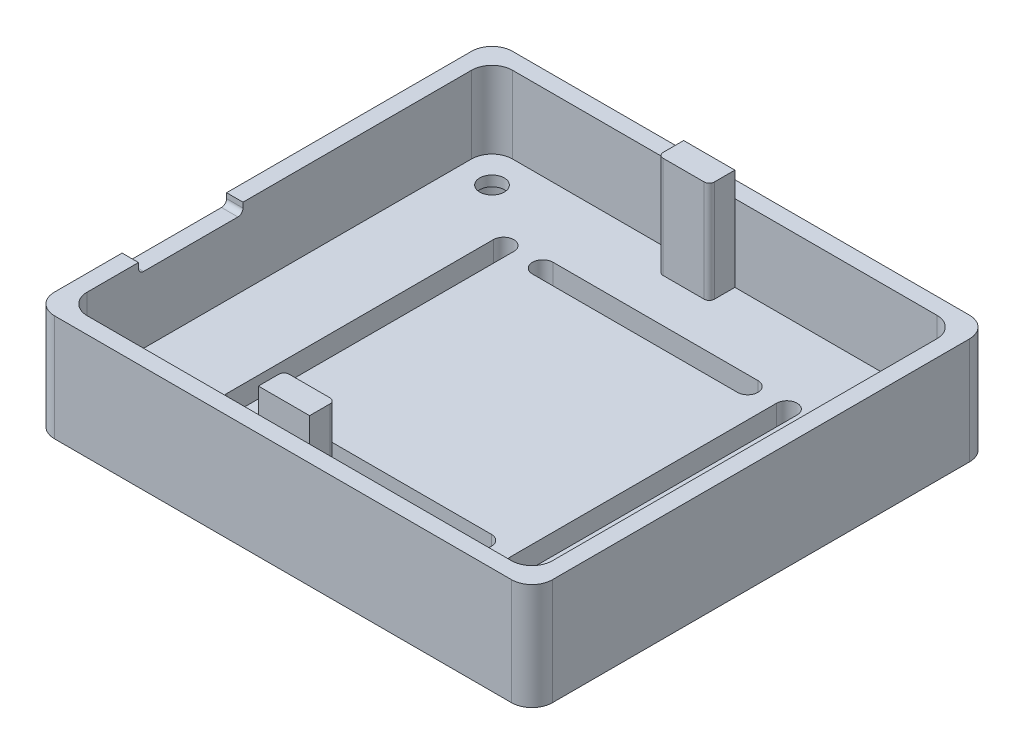
SolidWorks part; units mm, degrees
ref_plane "前视基准面" through (0, 0, 0) normal (0, 0, 1) x (1, 0, 0)
ref_plane "上视基准面" through (0, 0, 0) normal (0, 1, 0) x (1, 0, 0)
ref_plane "右视基准面" through (0, 0, 0) normal (1, 0, 0) x (0, 0, -1)
other "Configuration Table"
sketch "草图1" plane through (0, 0, 0) normal (0, 1, 0) x (1, 0, 0)
  line L1 (-22.3, -22.35) -> (22.3, -22.35)
  line L2 (-24.3, -20.35) -> (-24.3, 20.35)
  line L3 (-22.3, 22.35) -> (22.3, 22.35)
  line L4 (24.3, -20.35) -> (24.3, 20.35)
  line L5 (0, 22.35) -> (0, -22.35) construction
  line L6 (-24.3, 0) -> (24.3, 0) construction
  arc A0 (-22.3, -22.35) -> (-24.3, -20.35) centre (-22.3, -20.35) cw
  arc A1 (22.3, -22.35) -> (24.3, -20.35) centre (22.3, -20.35) ccw
  arc A2 (22.3, 22.35) -> (24.3, 20.35) centre (22.3, 20.35) cw
  arc A3 (-24.3, 20.35) -> (-22.3, 22.35) centre (-22.3, 20.35) cw
  point P0 (0, 0)
  point P6 (-24.3, -22.35)
  point P9 (24.3, -22.35)
  point P15 (-24.3, 22.35)
  dimension "D3" = 2
  dimension "D1" = 48.6
  dimension "D2" = 44.7
extrude "凸台-拉伸1" add sketch "草图1" along normal blind 10.4
sketch "草图2" plane through (0, 10.4, 0) normal (0, 1, 0) x (1, 0, 0)
  line L1 (-20.7, -20.75) -> (20.7, -20.75)
  line L2 (-22.7, -18.75) -> (-22.7, 18.75)
  line L3 (-20.7, 20.75) -> (20.7, 20.75)
  line L4 (22.7, -18.75) -> (22.7, 18.75)
  line L5 (0, 20.75) -> (0, -20.75) construction
  line L6 (-22.7, 0) -> (22.7, 0) construction
  arc A0 (20.7, -20.75) -> (22.7, -18.75) centre (20.7, -18.75) ccw
  arc A1 (-20.7, -20.75) -> (-22.7, -18.75) centre (-20.7, -18.75) cw
  arc A2 (20.7, 20.75) -> (22.7, 18.75) centre (20.7, 18.75) cw
  arc A3 (-22.7, 18.75) -> (-20.7, 20.75) centre (-20.7, 18.75) cw
  point P0 (0, 0)
  point P11 (22.7, 20.75)
  point P14 (-22.7, 20.75)
  dimension "D3" = 2
  dimension "D1" = 45.4
  dimension "D2" = 41.5
extrude "切除-拉伸1" cut sketch "草图2" against normal blind 7.5
sketch "草图3" plane through (0, 0, 0) normal (0, -1, 0) x (1, 0, 0)
  line L0 (-24.3, -20.35) -> (-24.3, 20.35) construction
  line L2 (22.3, -22.35) -> (-22.3, -22.35) construction
  line L3 (0, 0) -> (-33.4621, 0) construction
  line L4 (-1.5, 7.444) -> (-1.5, -25.453) construction
  line L5 (-22.7, -18.75) -> (-22.7, 18.75) construction
  circle A0 centre (-19.5, -17.55) radius 2.1
  circle A1 centre (-19.5, 17.55) radius 2.1
  circle A2 centre (16.5, 17.55) radius 2.1
  dimension "D1" = 4.8
  dimension "D2" = 4.8
  dimension "D3" = 21.2
extrude "切除-拉伸2" cut sketch "草图3" against normal blind 1.9
sketch "草图4" plane through (0, 0, 0) normal (0, -1, 0) x (1, 0, 0)
  line L0 (0, 0) -> (-34.7805, 0) construction
  line L1 (-1.5, 22.1974) -> (-1.5, -25.6414) construction
  line L2 (-22.7, -18.75) -> (-22.7, 18.75) construction
  circle A0 centre (-19.5, 17.55) radius 1.2
  circle A1 centre (-19.5, 17.55) radius 2.1 construction
  circle A2 centre (-19.5, -17.55) radius 1.2
  circle A3 centre (16.5, 17.55) radius 1.2
  dimension "D1" = 0
  dimension "D3" = 21.2
extrude "切除-拉伸3" cut sketch "草图4" against normal blind 3.2
sketch "草图5" plane through (0, 2.9, 0) normal (0, 1, 0) x (1, 0, 0)
  line L0 (-1.5, 23.6997) -> (-1.5, -24.5786) construction
  line L1 (-4, 20.75) -> (1, 20.75)
  line L2 (-4, 20.75) -> (-4, 18.75)
  line L3 (-3.5, 18.25) -> (0.5, 18.25)
  line L4 (1, 20.75) -> (1, 18.75)
  line L5 (-1.5, 18.25) -> (-1.5, 20.75) construction
  line L6 (-4, 19.75) -> (1, 19.75) construction
  line L7 (-22.7, 18.75) -> (-22.7, -18.75) construction
  line L8 (20.7, 20.75) -> (-20.7, 20.75) construction
  line L9 (-22.1142, 20.1642) -> (22.1142, -20.1642) construction
  line L14 (22.1142, 20.1642) -> (-22.1142, -20.1642) construction
  line L15 (0, 0) -> (30.1108, 0) construction
  line L16 (-19, -17.55) -> (17, -17.55) construction
  line L17 (20.7, 20.75) -> (-20.7, 20.75) construction
  line L19 (-3.5, -18.25) -> (0.5, -18.25)
  line L20 (1, -20.75) -> (1, -18.75)
  line L21 (-4, -20.75) -> (1, -20.75)
  line L22 (-4, -20.75) -> (-4, -18.75)
  arc A2 (0.5, 18.25) -> (1, 18.75) centre (0.5, 18.75) ccw
  arc A3 (-4, 18.75) -> (-3.5, 18.25) centre (-3.5, 18.75) ccw
  arc A4 (-20.7, 20.75) -> (-22.7, 18.75) centre (-20.7, 18.75) ccw construction
  arc A5 (20.7, -20.75) -> (22.7, -18.75) centre (20.7, -18.75) ccw construction
  arc A6 (22.7, 18.75) -> (20.7, 20.75) centre (20.7, 18.75) ccw construction
  arc A7 (-22.7, -18.75) -> (-20.7, -20.75) centre (-20.7, -18.75) ccw construction
  arc A9 (0.5, -18.25) -> (1, -18.75) centre (0.5, -18.75) cw
  arc A10 (-4, -18.75) -> (-3.5, -18.25) centre (-3.5, -18.75) cw
  point P0 (-1.5, 19.75)
  point P18 (1.5, -19.1037)
  point P21 (-3.5, -19.1037)
  point P24 (1, 18.25)
  point P27 (-4, 18.25)
  point P43 (-1.5, 0)
  point P45 (0, 0)
  point P46 (-1, -17.55)
  dimension "D1" = 21.2
  dimension "D2" = 2.5
  dimension "D3" = 5
  dimension "D7" = 20.75
extrude "凸台-拉伸2" add sketch "草图5" along normal blind 9.91
sketch "草图6" plane through (0, 0, 0) normal (0, -1, 0) x (1, 0, 0)
  line L0 (-13.8213, 13) -> (-13.8213, -13) construction
  line L1 (-12.8213, 13) -> (-12.8213, -13)
  line L2 (-14.8213, 13) -> (-14.8213, -13)
  line L3 (0, 0) -> (31.9618, 0) construction
  line L4 (-10, -13) -> (10, -13) construction
  line L7 (-10, -12) -> (10, -12)
  line L10 (-10, -14) -> (10, -14)
  line L13 (0, 0) -> (0, -24.7272) construction
  line L14 (13.8213, 13) -> (13.8213, -13) construction
  line L15 (12.8213, 13) -> (12.8213, -13)
  line L16 (14.8213, 13) -> (14.8213, -13)
  line L17 (-10, 13) -> (10, 13) construction
  line L18 (-10, 12) -> (10, 12)
  line L19 (-10, 14) -> (10, 14)
  arc A0 (-12.8213, 13) -> (-14.8213, 13) centre (-13.8213, 13) ccw
  arc A1 (-14.8213, -13) -> (-12.8213, -13) centre (-13.8213, -13) ccw
  arc A12 (-10, -12) -> (-10, -14) centre (-10, -13) ccw
  arc A13 (10, -14) -> (10, -12) centre (10, -13) ccw
  arc A14 (12.8213, 13) -> (14.8213, 13) centre (13.8213, 13) cw
  arc A15 (14.8213, -13) -> (12.8213, -13) centre (13.8213, -13) cw
  arc A16 (-10, 12) -> (-10, 14) centre (-10, 13) cw
  arc A17 (10, 14) -> (10, 12) centre (10, 13) cw
  point P2 (-13.8213, 0)
  point P11 (0, -13)
  point P22 (13.8213, 0)
  point P29 (0, 13)
  dimension "D2" = 10
  dimension "D1" = 26
  dimension "D3" = 13
extrude "切除-拉伸4" cut sketch "草图6" against normal blind 10
sketch "草图7" plane through (-24.3, 0, 0) normal (-1, 0, 0) x (0, 0, 1)
  line L0 (-20.75, 2.9) -> (-20.75, 10.4) construction
  line L1 (3.55, 10.4) -> (13.75, 10.4)
  line L2 (3.55, 10.4) -> (3.55, 9.9)
  line L3 (4.05, 9.4) -> (13.25, 9.4)
  line L4 (13.75, 10.4) -> (13.75, 9.9)
  line L5 (8.65, 9.4) -> (8.65, 10.4) construction
  line L6 (3.55, 10.15) -> (13.75, 10.15) construction
  line L8 (-20.35, 10.4) -> (20.35, 10.4) construction
  arc A0 (13.25, 9.4) -> (13.75, 9.9) centre (13.25, 9.9) ccw
  arc A1 (3.55, 9.9) -> (4.05, 9.4) centre (4.05, 9.9) ccw
  point P0 (8.65, 10.15)
  point P10 (13.75, 9.4)
  point P13 (3.55, 9.4)
  dimension "D5" = 0.5
  dimension "D1" = 29.4
  dimension "D2" = 10.2
  dimension "D3" = 1
  dimension "D4" = 0
extrude "切除-拉伸5" cut sketch "草图7" against normal blind 10
